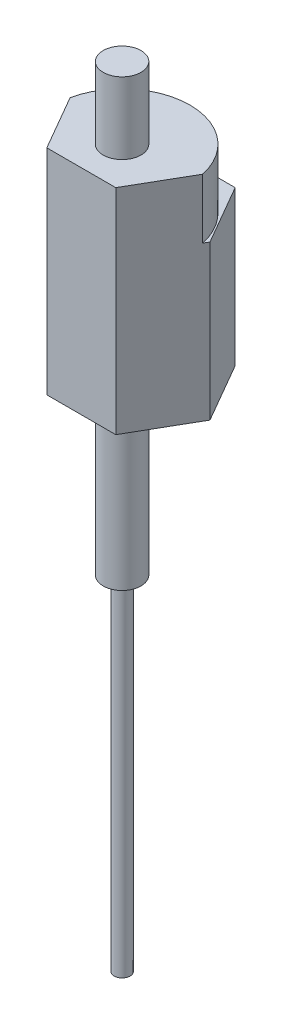
SolidWorks part; units mm, degrees
ref_plane "Front Plane" through (0, 0, 0) normal (0, 0, 1) x (1, 0, 0)
ref_plane "Top Plane" through (0, 0, 0) normal (0, 1, 0) x (1, 0, 0)
ref_plane "Right Plane" through (0, 0, 0) normal (1, 0, 0) x (0, 0, -1)
sketch "Sketch1" plane through (0, 0, 0) normal (0, 1, 0) x (1, 0, 0)
  line L1 (-6.9282, 0) -> (-3.4641, -6)
  line L2 (-3.4641, -6) -> (3.4641, -6)
  line L3 (3.4641, -6) -> (6.9282, 0)
  line L4 (6.9282, 0) -> (3.4641, 6)
  line L5 (3.4641, 6) -> (-3.4641, 6)
  line L6 (-3.4641, 6) -> (-6.9282, 0)
  circle A0 centre (0, 0) radius 6 construction
  dimension "D1" = 12
extrude "Boss-Extrude1" add sketch "Sketch1" along normal blind 21.5
sketch "Sketch2" plane through (0, 21.5, 0) normal (0, 1, 0) x (1, 0, 0)
  line L1 (-3.4641, -6) -> (3.4641, -6) construction
  circle A0 centre (0, -1.9) radius 1.9
  dimension "D1" = 3.8
  dimension "D2" = 4.1
extrude "Boss-Extrude2" add sketch "Sketch2" along normal blind 7.2
sketch "Sketch3" plane through (0, 21.5, 0) normal (0, 1, 0) x (1, 0, 0)
  line L0 (3.4641, 6) -> (-3.4641, 6) construction
  line L2 (3.4641, -6) -> (6.9282, 0) construction
  line L4 (-6.6615, -0.4619) -> (-6.9282, 0)
  line L5 (-6.9282, 0) -> (-3.4641, 6)
  line L6 (-3.4641, 6) -> (3.4641, 6)
  line L7 (3.4641, 6) -> (6.9282, 0)
  line L8 (6.9282, 0) -> (6.6615, -0.4619)
  arc A0 (6.6615, -0.4619) -> (-6.6615, -0.4619) centre (0, -1.9) ccw
  point P3 (0, 6)
extrude "Cut-Extrude1" cut sketch "Sketch3" against normal blind 6
sketch "Sketch4" plane through (0, 0, 0) normal (0, -1, 0) x (1, 0, 0)
  circle A0 centre (0, 1.9) radius 1.9
extrude "Boss-Extrude3" add sketch "Sketch4" along normal blind 16
sketch "Sketch5" plane through (0, -16, 0) normal (0, -1, 0) x (1, 0, 0)
  circle A0 centre (0, 1.9) radius 0.8
  circle A1 centre (0, 1.9) radius 0.6548
extrude "Boss-Extrude4" add sketch "Sketch5" along normal blind 34.5
